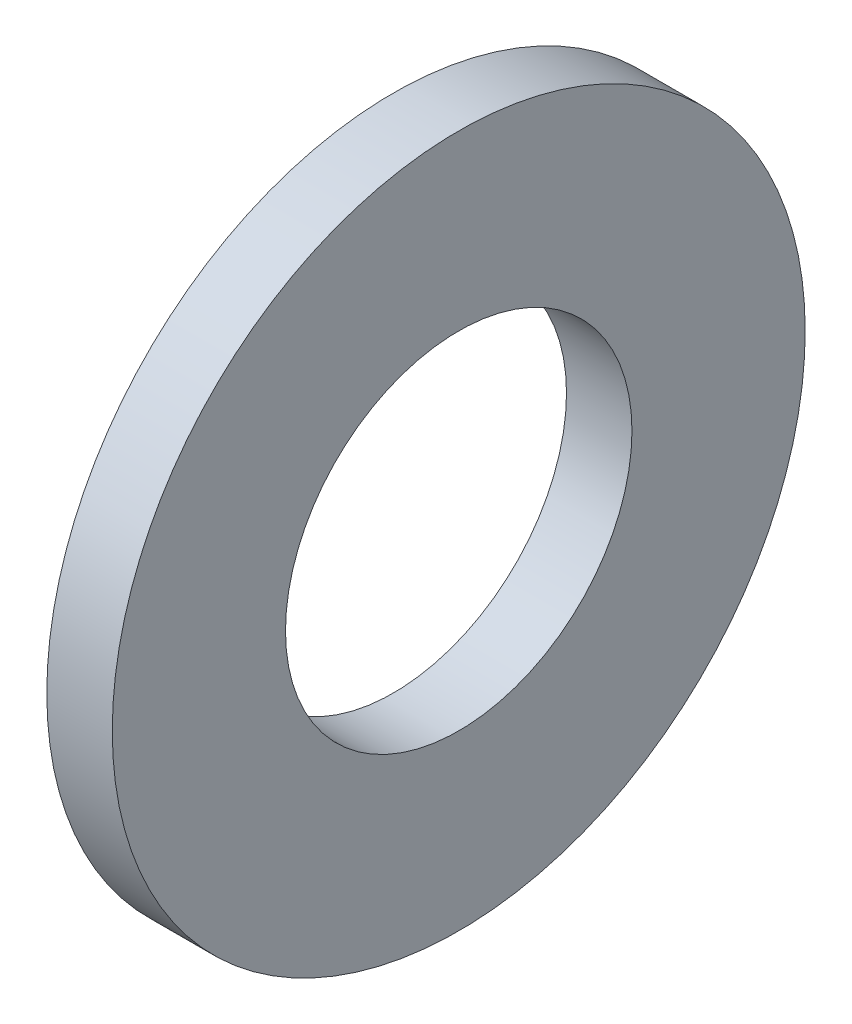
SolidWorks part; units mm, degrees
ref_plane "Plane1" through (0, 0, 0) normal (0, 0, 1) x (1, 0, 0)
ref_plane "Plane2" through (0, 0, 0) normal (0, 1, 0) x (1, 0, 0)
ref_plane "Plane3" through (0, 0, 0) normal (1, 0, 0) x (0, 0, -1)
sketch "Sketch1" plane through (0, 0, 0) normal (0, 0, 1) x (1, 0, 0)
  line L0 (-34.925, 0) -> (9.525, 0) construction
  line L1 (0, 4.3688) -> (0, 8.7376)
  line L2 (0, 8.7376) -> (-1.651, 8.7376)
  line L3 (-1.651, 8.7376) -> (-1.651, 4.3688)
  line L4 (-1.651, 4.3688) -> (0, 4.3688)
  dimension "Thickness" = 1.651
  dimension "Inside_dia" = 8.7376
  dimension "Outside_dia" = 17.4752
revolve "Base-Revolve" add sketch "Sketch1" angle 360 about L0
